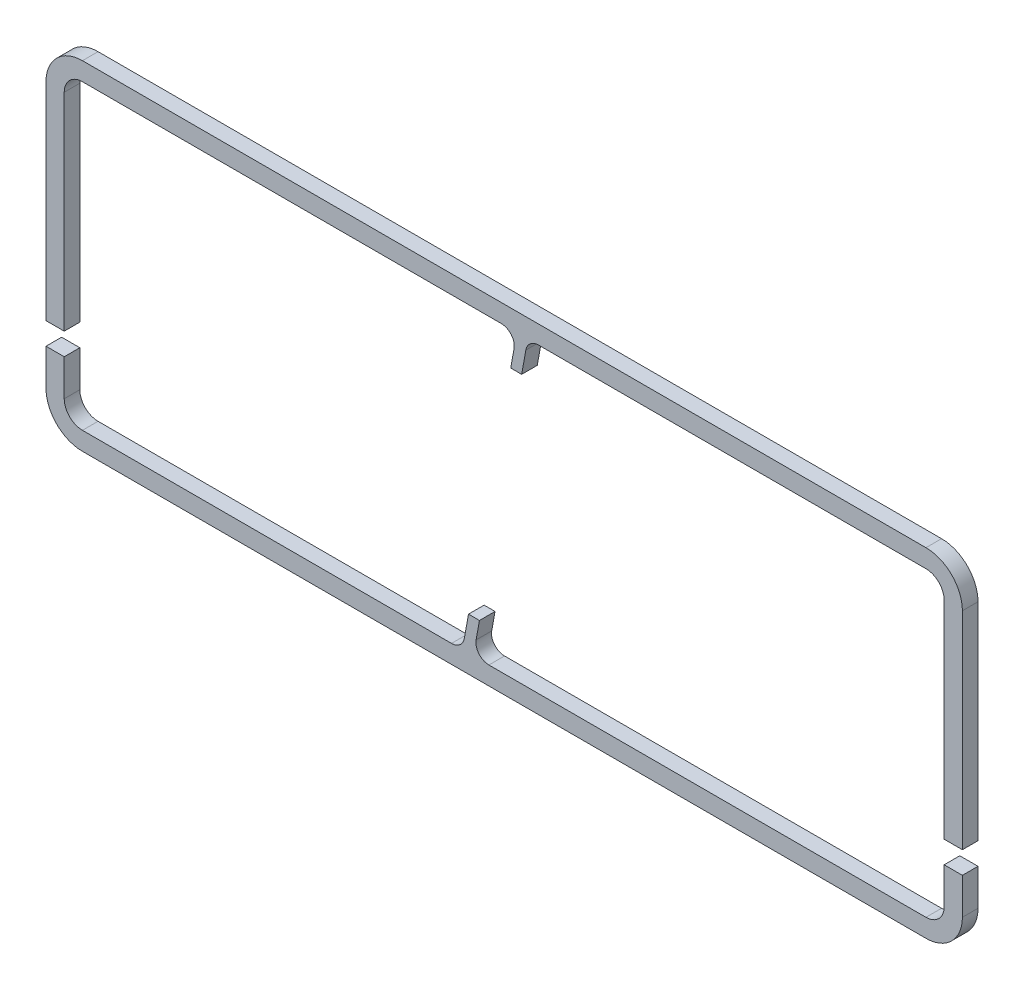
SolidWorks part; units mm, degrees
material "Maple"
ref_plane "Alzado" through (0, 0, 0) normal (0, 0, 1) x (1, 0, 0)
ref_plane "Planta" through (0, 0, 0) normal (0, 1, 0) x (1, 0, 0)
ref_plane "Vista lateral" through (0, 0, 0) normal (1, 0, 0) x (0, 0, -1)
sketch "Croquis1" plane through (0, 0, 0) normal (0, 0, 1) x (1, 0, 0)
  line L0 (-162.0605, 58) -> (-1.1291, 58)
  line L1 (-162.0605, 65) -> (162.0605, 65)
  line L2 (-176.0605, 51) -> (-176.0605, -28.52)
  line L3 (-162.0605, -65) -> (162.0605, -65)
  line L4 (176.0605, 51) -> (176.0605, -28.52)
  line L5 (-176.0605, 65) -> (176.0605, -65) construction
  line L6 (-176.0605, -65) -> (176.0605, 65) construction
  line L7 (169.0605, 51) -> (169.0605, -28.52)
  line L8 (-162.0605, -58) -> (-20.2397, -58)
  line L9 (-169.0605, 51) -> (-169.0605, -28.52)
  line L10 (3.7916, 52.1129) -> (2.5092, 45)
  line L11 (8.319, 53.8871) -> (6.7167, 45)
  line L12 (13.2397, 58) -> (162.0605, 58)
  line L13 (-162.0605, 58) -> (162.0605, 58) construction
  line L14 (-5.8709, -58) -> (162.0605, -58)
  line L15 (-162.0605, -58) -> (162.0605, -58) construction
  line L16 (6.7167, 45) -> (2.5092, 45)
  line L17 (-13.7167, -45) -> (-9.5092, -45)
  line L18 (-176.0605, -28.52) -> (-169.0605, -28.52)
  line L19 (-176.0605, -37.02) -> (-169.0605, -37.02)
  line L20 (-9.5092, -45) -> (-10.7916, -52.1129)
  line L21 (-13.7167, -45) -> (-15.319, -53.8871)
  line L22 (-169.0605, -37.02) -> (-169.0605, -51)
  line L23 (-169.0605, 51) -> (-169.0605, -51) construction
  line L24 (-176.0605, -37.02) -> (-176.0605, -51)
  line L25 (-176.0605, 51) -> (-176.0605, -51) construction
  line L26 (169.0605, -28.52) -> (176.0605, -28.52)
  line L27 (169.0605, -37.02) -> (176.0605, -37.02)
  line L28 (176.0605, -37.02) -> (176.0605, -51)
  line L29 (176.0605, 51) -> (176.0605, -51) construction
  line L30 (169.0605, -37.02) -> (169.0605, -51)
  line L31 (169.0605, 51) -> (169.0605, -51) construction
  arc A0 (162.0605, 65) -> (176.0605, 51) centre (162.0605, 51) cw
  arc A1 (162.0605, -65) -> (176.0605, -51) centre (162.0605, -51) ccw
  arc A2 (-176.0605, -51) -> (-162.0605, -65) centre (-162.0605, -51) ccw
  arc A3 (-162.0605, 65) -> (-176.0605, 51) centre (-162.0605, 51) ccw
  circle A4 centre (-165.0005, 53.94) radius 1.5 construction
  arc A5 (162.0605, 58) -> (169.0605, 51) centre (162.0605, 51) cw
  arc A6 (162.0605, -58) -> (169.0605, -51) centre (162.0605, -51) ccw
  arc A7 (-169.0605, -51) -> (-162.0605, -58) centre (-162.0605, -51) ccw
  arc A8 (-162.0605, 58) -> (-169.0605, 51) centre (-162.0605, 51) ccw
  circle A9 centre (-0.0005, 53.94) radius 1.5 construction
  circle A10 centre (164.9995, 53.94) radius 1.5 construction
  circle A11 centre (-165.0005, -53.96) radius 1.5 construction
  circle A12 centre (-0.0005, -53.96) radius 1.5 construction
  circle A13 centre (164.9995, -53.96) radius 1.5 construction
  arc A14 (8.319, 53.8871) -> (13.2397, 58) centre (13.2397, 53) cw
  arc A15 (-10.7916, -52.1129) -> (-5.8709, -58) centre (-5.8709, -53) ccw
  arc A16 (-15.319, -53.8871) -> (-20.2397, -58) centre (-20.2397, -53) cw
  arc A17 (3.7916, 52.1129) -> (-1.1291, 58) centre (-1.1291, 53) ccw
  point P0 (0, 0)
  point P49 (9.0605, 58)
  point P52 (-11.853, -58)
  point P55 (-16.0605, -58)
  point P65 (-172.5605, -37.02)
  dimension "D3" = 14
  dimension "D4" = 11.06
  dimension "D5" = 11.06
  dimension "D6" = 3
  dimension "D10" = 165
  dimension "D11" = 4.06
  dimension "D12" = 11.04
  dimension "D18" = 5
  dimension "D1" = 352.121
  dimension "D2" = 130
  dimension "D13" = 11.06
  dimension "D14" = 160
  dimension "D15" = 160
  dimension "D16" = 100.22
  dimension "D17" = 100.22
  dimension "D19" = 20
  dimension "D20" = 20
  dimension "D21" = 79.78
  dimension "D22" = 100.22
  dimension "D23" = 8.5
  dimension "D24" = 27.98
  dimension "D25" = 27.98
  dimension "D26" = 8.5
  dimension "D7" = 7
  dimension "D8" = 3
  dimension "D9" = 2
extrude "Saliente-Extruir3" add sketch "Croquis1" along normal blind 6
sketch "Croquis3" plane through (0, 0, 6) normal (0, 0, 1) x (1, 0, 0)
  line L0 (0, 0) -> (0, 65) construction
  line L1 (162.0605, 65) -> (-162.0605, 65) construction
